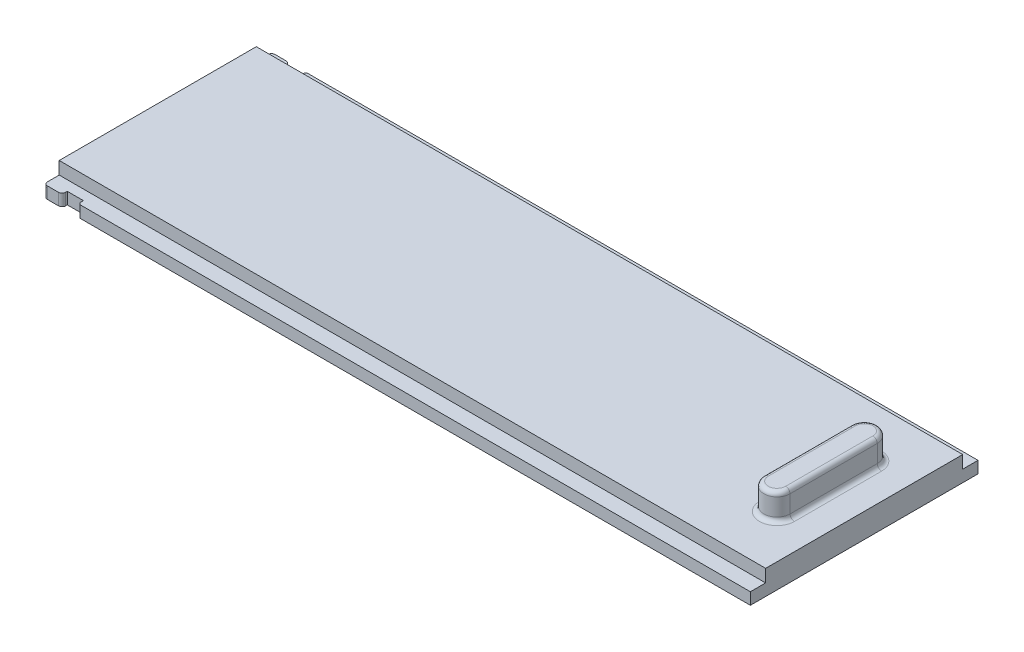
SolidWorks part; units mm, degrees
ref_plane "Front Plane" through (0, 0, 0) normal (0, 0, 1) x (1, 0, 0)
ref_plane "Top Plane" through (0, 0, 0) normal (0, 1, 0) x (1, 0, 0)
ref_plane "Right Plane" through (0, 0, 0) normal (1, 0, 0) x (0, 0, -1)
sketch "Sketch1" plane through (0, 0, 0) normal (0, 1, 0) x (1, 0, 0)
  line L1 (0, 0) -> (81, 0)
  line L2 (0, 0) -> (0, 29)
  line L3 (0, 29) -> (81, 29)
  line L4 (81, 0) -> (81, 29)
  dimension "D1" = 29
  dimension "D2" = 81
extrude "Boss-Extrude1" add sketch "Sketch1" along normal blind 3
sketch "Sketch2" plane through (81, 0, 0) normal (1, 0, 0) x (0, 0, -1)
  line L0 (0, 0) -> (29, 0) construction
  line L1 (0, 3) -> (3, 3)
  line L2 (0, 3) -> (0, 0)
  line L3 (0, 0) -> (1.25, 0)
  line L4 (3, 3) -> (3, 1.75)
  line L5 (3, 1.75) -> (1.25, 1.75)
  line L6 (1.25, 1.75) -> (1.25, 0)
  line L11 (14.5, 3) -> (14.5, 0) construction
  line L12 (0, 3) -> (29, 3) construction
  line L21 (29, 0) -> (27.75, 0)
  line L22 (29, 3) -> (26, 3)
  line L25 (27.75, 1.75) -> (26, 1.75)
  line L26 (26, 1.75) -> (26, 3)
  line L31 (27.75, 1.75) -> (27.75, 0)
  line L35 (29, 3) -> (29, 0)
  dimension "D1" = 1.25
  dimension "D2" = 1.25
  dimension "D3" = 3
extrude "Cut-Extrude2" cut sketch "Sketch2" against normal up to surface (81 mm away) up to face at (0, 1.5, -14.5)
sketch "Sketch4" plane through (81, 0, 0) normal (1, 0, 0) x (0, 0, -1)
  line L6 (27.75, 0) -> (27.55, 0)
  line L8 (27.75, 1.75) -> (27.75, 0)
  line L17 (14.5, 3) -> (14.5, 0) construction
  line L18 (3, 3) -> (26, 3) construction
  line L19 (1.25, 0) -> (27.75, 0) construction
  line L32 (25.8, 1.55) -> (25.8, 3)
  line L33 (27.55, 1.55) -> (25.8, 1.55)
  line L34 (27.55, 0) -> (27.55, 1.55)
  line L35 (26, 1.75) -> (27.75, 1.75)
  line L36 (26, 3) -> (26, 1.75)
  line L37 (25.8, 3) -> (26, 3)
  line L44 (3.2, 3) -> (3, 3)
  line L45 (3, 3) -> (3, 1.75)
  line L46 (3, 1.75) -> (1.25, 1.75)
  line L47 (1.45, 0) -> (1.45, 1.55)
  line L48 (1.45, 1.55) -> (3.2, 1.55)
  line L49 (3.2, 1.55) -> (3.2, 3)
  line L50 (1.45, 0) -> (1.45, 1.55)
  line L51 (1.45, 1.55) -> (3.2, 1.55)
  line L52 (3.2, 1.55) -> (3.2, 3)
  line L53 (1.25, 1.75) -> (1.25, 0)
  line L54 (1.25, 0) -> (1.45, 0)
  dimension "D1" = 0.2
extrude "Cut-Extrude3" cut sketch "Sketch4" against normal up to surface (81 mm away) up to face at (0, 1.625, -14.5)
sketch "Sketch6" plane through (0, 0, -1.45) normal (0, 0, 1) x (1, 0, 0)
  line L0 (0, 0.775) -> (3, 0.775) construction
  line L3 (2.075, 0) -> (3.925, 0)
  line L4 (2.075, 0) -> (2.075, 1.55)
  line L5 (2.075, 1.55) -> (3.925, 1.55)
  line L6 (3.925, 0) -> (3.925, 1.55)
  line L7 (2.075, 0) -> (3.925, 1.55) construction
  line L8 (2.075, 1.55) -> (3.925, 0) construction
  line L11 (0, 1.55) -> (81, 1.55) construction
  line L12 (0, 1.55) -> (0, 0) construction
  dimension "D1" = 3
  dimension "D3" = 1.85
  dimension "D4" = 0.775
extrude "Cut-Extrude5" cut sketch "Sketch6" against normal blind 0.6
fillet "Fillet6" radius 0.4 1 edges at (2.075, 0.775, -1.45)
chamfer "Chamfer2" distance 0.2 angle 45 1 edges at (3.925, 0.775, -1.45)
sketch "Sketch7" plane through (0, 0, -27.55) normal (0, 0, -1) x (-1, 0, 0)
  line L0 (-3, 0.775) -> (0, 0.775) construction
  line L3 (-2.075, 1.55) -> (-3.925, 1.55)
  line L4 (-2.075, 1.55) -> (-2.075, 0)
  line L5 (-2.075, 0) -> (-3.925, 0)
  line L6 (-3.925, 1.55) -> (-3.925, 0)
  line L7 (-2.075, 1.55) -> (-3.925, 0) construction
  line L8 (-2.075, 0) -> (-3.925, 1.55) construction
  line L9 (0, 1.55) -> (-81, 1.55) construction
  line L10 (0, 0) -> (0, 1.55) construction
  dimension "D1" = 3
  dimension "D3" = 1.85
  dimension "D4" = 0.775
extrude "Cut-Extrude6" cut sketch "Sketch7" against normal blind 0.6
fillet "Fillet7" radius 0.4 1 edges at (2.075, 0.775, -27.55)
chamfer "Chamfer3" distance 0.2 angle 45 1 edges at (3.925, 0.775, -27.55)
sketch "Sketch9" plane through (0, 3, 0) normal (0, 1, 0) x (1, 0, 0)
  line L0 (76, 9.5) -> (76, 19.5) construction
  line L1 (74.5, 9.5) -> (74.5, 19.5)
  line L2 (77.5, 9.5) -> (77.5, 19.5)
  line L3 (76, 8) -> (76, 3.2) construction
  line L5 (0, 3.2) -> (81, 3.2) construction
  line L14 (76, 21) -> (76, 25.8) construction
  line L15 (0, 25.8) -> (81, 25.8) construction
  line L16 (81, 3.2) -> (81, 25.8) construction
  arc A0 (74.5, 9.5) -> (77.5, 9.5) centre (76, 9.5) ccw
  arc A1 (77.5, 19.5) -> (74.5, 19.5) centre (76, 19.5) ccw
  point P2 (76, 14.5)
  dimension "D1" = 3
  dimension "D2" = 10
  dimension "D3" = 5
sketch "Sketch11" plane through (0, 0, 0) normal (0, -1, 0) x (-1, 0, 0)
  line L1 (0, 27.55) -> (-81, 27.55)
  line L2 (0, 27.55) -> (0, 1.45)
  line L3 (0, 1.45) -> (-81, 1.45)
  line L4 (-81, 27.55) -> (-81, 1.45)
extrude "Cut-Extrude7" cut sketch "Sketch11" against normal blind 0.2
fillet "Fillet8" radius 0.4 2 edges at (0, 0.875, -27.55) (0, 0.875, -1.45)
extrude "Boss-Extrude2" add sketch "Sketch9" along normal blind 3
fillet "Fillet11" radius 0.5 4 edges at (74.5, 6, -14.5) (76, 6, -21) (77.5, 6, -14.5) (76, 6, -8)
fillet "Fillet10" radius 0.5 4 edges at (74.5, 3, -14.5) (76, 3, -21) (77.5, 3, -14.5) (76, 3, -8)
